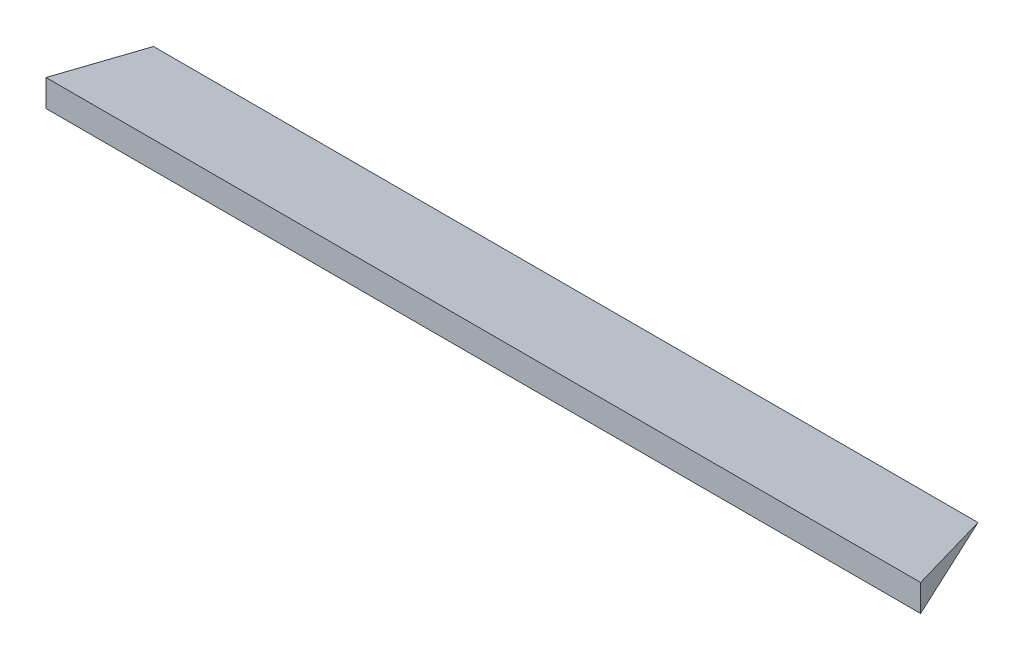
SolidWorks part; units mm, degrees
material "Balsa"
ref_plane "Front Plane" through (0, 0, 0) normal (0, 0, 1) x (1, 0, 0)
ref_plane "Top Plane" through (0, 0, 0) normal (0, 1, 0) x (1, 0, 0)
ref_plane "Right Plane" through (0, 0, 0) normal (1, 0, 0) x (0, 0, -1)
sketch "Sketch1" plane through (0, 0, 0) normal (1, 0, 0) x (0, 0, -1)
  line L0 (0, 0) -> (38.1, 0)
  line L1 (38.1, 0) -> (0, 9.525)
  line L2 (0, 9.525) -> (0, 0)
  dimension "D1" = 38.1
  dimension "D2" = 9.525
extrude "Boss-Extrude1" add sketch "Sketch1" along normal blind 310
sketch "Sketch3" plane through (0, 0, 0) normal (0, 1, 0) x (1, 0, 0)
  line L0 (310, 0) -> (292.2337, 38.1)
  line L1 (310, 38.1) -> (0, 38.1) construction
  line L2 (292.2337, 38.1) -> (310, 38.1)
  line L3 (310, 38.1) -> (310, 0)
  dimension "D1" = 25
extrude "Cut-Extrude1" cut sketch "Sketch3" along normal through all both and the other way through all
